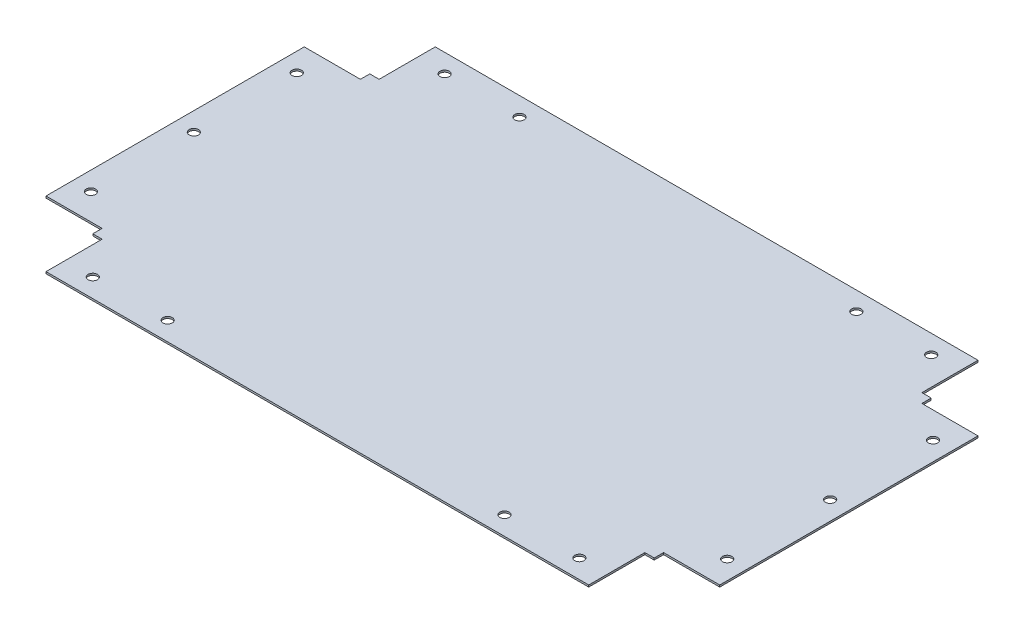
SolidWorks part; units mm, degrees
ref_plane "Front Plane" through (0, 0, 0) normal (0, 0, 1) x (1, 0, 0)
ref_plane "Top Plane" through (0, 0, 0) normal (0, 1, 0) x (1, 0, 0)
ref_plane "Right Plane" through (0, 0, 0) normal (1, 0, 0) x (0, 0, -1)
sketch "Sketch1" plane through (0, 0, 0) normal (0, 1, 0) x (1, 0, 0)
  line L0 (0, 0) -> (0, 5)
  line L1 (0, 0) -> (300, 0) construction
  line L2 (0, 0) -> (0, 148) construction
  line L3 (0, 148) -> (300, 148) construction
  line L4 (300, 0) -> (300, 148) construction
  line L5 (0, 5) -> (-30, 5)
  line L6 (-30, 5) -> (-30, 143)
  line L7 (-30, 143) -> (0, 143)
  line L8 (0, 143) -> (0, 148)
  line L9 (0, 148) -> (5, 148)
  line L10 (5, 148) -> (5, 178)
  line L11 (5, 178) -> (295, 178)
  line L12 (295, 178) -> (295, 148)
  line L13 (295, 148) -> (300, 148)
  line L14 (300, 148) -> (300, 143)
  line L15 (300, 143) -> (330, 143)
  line L16 (330, 143) -> (330, 5)
  line L17 (330, 5) -> (300, 5)
  line L18 (300, 5) -> (300, 0)
  line L19 (300, 0) -> (295, 0)
  line L20 (295, 0) -> (295, -30)
  line L21 (295, -30) -> (5, -30)
  line L22 (5, -30) -> (5, 0)
  line L23 (5, 0) -> (0, 0)
  line L24 (0, 74) -> (-30, 74) construction
  line L25 (0, 74) -> (300, 74) construction
  line L26 (300, 74) -> (330, 74) construction
  line L27 (150, -30) -> (150, 0) construction
  line L28 (150, 0) -> (150, 74) construction
  line L29 (150, 74) -> (150, 148) construction
  line L30 (150, 148) -> (150, 178) construction
  line L31 (-20, 5) -> (-20, 143) construction
  line L32 (-20, 19) -> (320, 19) construction
  line L33 (5, 168) -> (295, 168) construction
  line L34 (20, -20) -> (20, 168) construction
  line L35 (320, 143) -> (320, 5) construction
  line L36 (-20, 129) -> (320, 129) construction
  line L37 (295, -20) -> (5, -20) construction
  line L39 (280, -20) -> (280, 168) construction
  circle A0 centre (20, -20) radius 2.5
  circle A1 centre (60, -20) radius 2.5
  circle A2 centre (280, -20) radius 2.5
  circle A3 centre (240, -20) radius 2.5
  circle A4 centre (320, 19) radius 2.5
  circle A6 centre (320, 129) radius 2.5
  circle A8 centre (280, 168) radius 2.5
  circle A9 centre (240, 168) radius 2.5
  circle A10 centre (60, 168) radius 2.5
  circle A11 centre (20, 168) radius 2.5
  circle A12 centre (-20, 129) radius 2.5
  circle A14 centre (-20, 19) radius 2.5
  circle A15 centre (-20, 74) radius 2.5
  circle A16 centre (320, 74) radius 2.5
  dimension "D3" = 55
  dimension "D16" = 5
  dimension "D1" = 148
  dimension "D2" = 300
  dimension "D4" = 55
  dimension "D5" = 40
  dimension "D6" = 20
  dimension "D7" = 5
  dimension "D8" = 5
  dimension "D9" = 30
  dimension "D10" = 40
  dimension "D11" = 20
  dimension "D12" = 20
  dimension "D13" = 20
  dimension "D14" = 30
  dimension "D15" = 30
  dimension "D17" = 20
  dimension "D18" = 20
  dimension "D19" = 5
  dimension "D20" = 30
  dimension "D21" = 40
  dimension "D22" = 40
extrude "Boss-Extrude1" add sketch "Sketch1" along normal blind 1
